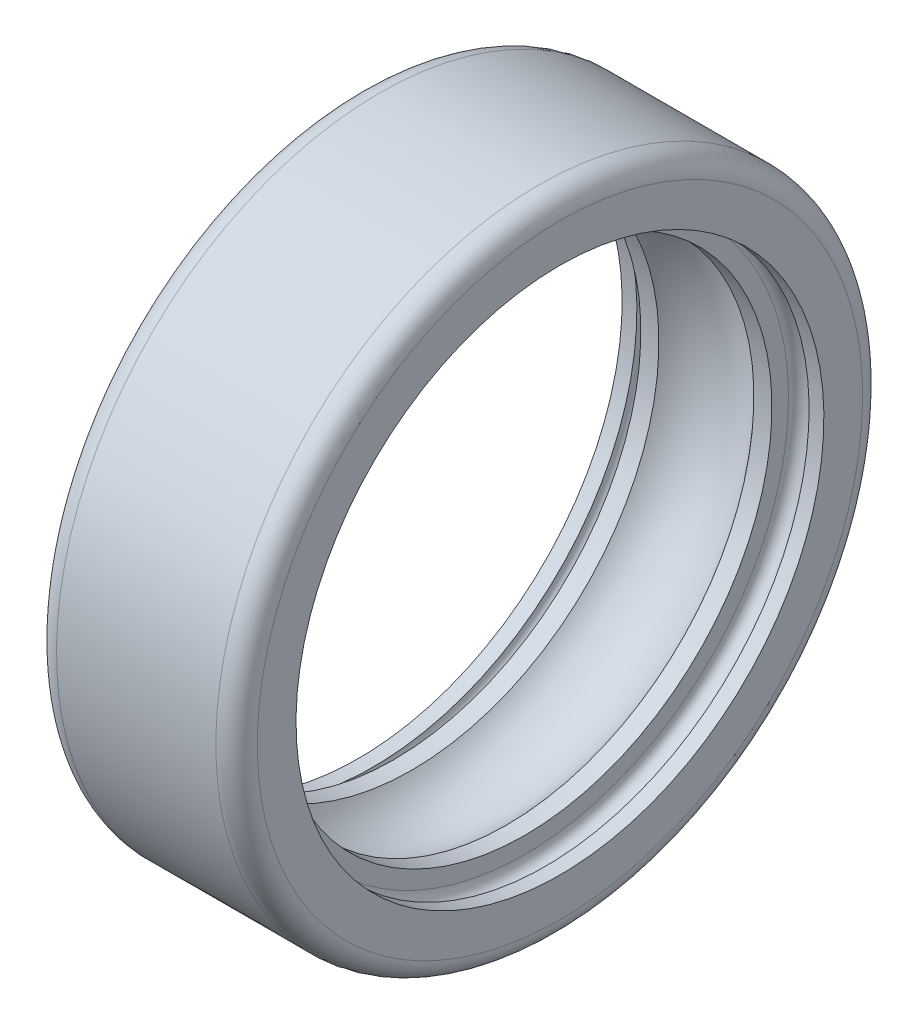
SolidWorks part; units mm, degrees
material "AISI 304"
ref_plane "Plano frontal" through (0, 0, 0) normal (0, 0, 1) x (1, 0, 0)
ref_plane "Plano superior" through (0, 0, 0) normal (0, 1, 0) x (1, 0, 0)
ref_plane "Plano direito" through (0, 0, 0) normal (1, 0, 0) x (0, 0, -1)
sketch "Esboço1" plane through (0, 0, 0) normal (0, 0, 1) x (1, 0, 0)
  line L0 (-22.7175, 2.9568) -> (-17.7175, 2.9568) construction
  line L2 (-1.9877, 2.5015) -> (1.957, 2.5015)
  line L3 (-2.4969, 3.0019) -> (-2.4969, 3.9651)
  line L4 (-1.9705, 8.0015) -> (1.9743, 8.0015)
  line L5 (2.5, 3.0019) -> (2.5, 3.9651)
  line L7 (-2.5, 6.5408) -> (-2.1334, 6.5408)
  line L8 (-1.6236, 6.5408) -> (-1.6236, 6.1298)
  line L9 (-1.6236, 6.1298) -> (-1.1769, 6.1298)
  line L10 (1.6236, 6.1298) -> (1.1769, 6.1298)
  line L11 (1.6236, 6.5408) -> (1.6236, 6.1298)
  line L12 (2.5, 6.5408) -> (2.1334, 6.5408)
  line L13 (-2.1884, 4.1901) -> (-2.1884, 6.0268)
  line L14 (-2.1184, 6.0968) -> (-1.7245, 6.0968)
  line L15 (-1.6545, 6.1668) -> (-1.6545, 6.4667)
  line L16 (-2.1145, 6.4667) -> (-2.1145, 6.3275)
  line L17 (-2.078, 6.2794) -> (-1.8845, 6.2794)
  line L18 (-1.8845, 6.2794) -> (-1.8845, 6.3794)
  line L19 (-1.8845, 6.3794) -> (-1.9445, 6.3794)
  line L20 (-2.0145, 6.4494) -> (-2.0145, 6.4667)
  line L21 (-1.7545, 6.4667) -> (-1.7545, 6.2668)
  line L22 (-1.8245, 6.1968) -> (-2.2192, 6.1968)
  line L23 (-2.1188, 4.1201) -> (-1.9112, 4.1201)
  line L24 (-1.9112, 4.1201) -> (-1.9112, 4.0201)
  line L25 (-1.9112, 4.0201) -> (-2.2184, 4.0201)
  line L26 (-2.2884, 4.0901) -> (-2.2884, 6.0268)
  line L27 (-2.2884, 6.0268) -> (-2.2884, 6.1371)
  line L28 (-2.5, 6.5408) -> (-2.5, 7.5)
  line L29 (2.5, 6.5408) -> (2.5, 7.5)
  line L30 (-2.4969, 3.9651) -> (-2.2384, 3.9651)
  line L31 (-2.2384, 3.9651) -> (-2.0732, 3.7803)
  line L32 (-2.0732, 3.7803) -> (-1.8146, 3.7803)
  line L33 (-1.8146, 3.7803) -> (-1.8146, 4.2124)
  line L34 (-1.8146, 4.2124) -> (-1.2851, 4.4263)
  line L35 (1.8146, 4.2124) -> (1.2851, 4.4263)
  line L36 (1.8146, 3.7803) -> (1.8146, 4.2124)
  line L37 (2.0732, 3.7803) -> (1.8146, 3.7803)
  line L38 (2.2384, 3.9651) -> (2.0732, 3.7803)
  line L39 (2.5, 3.9651) -> (2.2384, 3.9651)
  line L40 (0, 0.0015) -> (-3.7152, 0) construction
  line L41 (0, 0.0015) -> (0, 8) construction
  arc A0 (-2.1334, 6.5408) -> (-1.6236, 6.5408) centre (-1.8785, 6.5408) cw
  arc A1 (-1.2851, 4.4263) -> (1.2851, 4.4263) centre (0, 5.1999) ccw
  arc A2 (2.1334, 6.5408) -> (1.6236, 6.5408) centre (1.8785, 6.5408) ccw
  arc A3 (-2.1884, 6.0268) -> (-2.1184, 6.0968) centre (-2.1184, 6.0268) cw
  arc A4 (-1.6545, 6.4667) -> (-2.1145, 6.4667) centre (-1.8845, 6.4667) ccw
  arc A5 (-2.1145, 6.3275) -> (-2.078, 6.2794) centre (-2.0459, 6.3416) ccw
  arc A6 (-2.0145, 6.4667) -> (-1.7545, 6.4667) centre (-1.8845, 6.4667) cw
  arc A7 (-2.2192, 6.1968) -> (-2.2884, 6.1371) centre (-2.2192, 6.1268) ccw
  arc A8 (1.1769, 6.1298) -> (-1.1769, 6.1298) centre (0, 5.1999) ccw
  arc A9 (-1.9877, 2.5015) -> (-2.4969, 3.0019) centre (-1.9969, 3.0014) cw
  arc A10 (1.957, 2.5015) -> (2.5, 3.0019) centre (2, 2.9996) ccw
  arc A11 (1.9743, 8.0015) -> (2.5, 7.5) centre (2, 7.5021) cw
  arc A12 (-2.5, 7.5) -> (-1.9705, 8.0015) centre (-2, 7.5024) cw
  arc A13 (-2.1884, 4.1901) -> (-2.1188, 4.1201) centre (-2.1184, 4.1901) ccw
  arc A14 (-2.2184, 4.0201) -> (-2.2884, 4.0901) centre (-2.2184, 4.0901) cw
  arc A15 (-1.9445, 6.3794) -> (-2.0145, 6.4494) centre (-1.9445, 6.4494) cw
  arc A16 (-1.7545, 6.2668) -> (-1.8245, 6.1968) centre (-1.8245, 6.2668) cw
  arc A17 (-1.7245, 6.0968) -> (-1.6545, 6.1668) centre (-1.7245, 6.1668) ccw
  point P7 (0, 0)
  point P9 (0, 0)
  point P10 (0, 0)
  point P11 (0, 0)
  point P12 (0, 0)
  point P22 (0, 0)
  point P30 (-2.1145, 6.4667)
  point P52 (0, 0)
  point P53 (0, 0)
  point P58 (2.5, 2.75)
  point P61 (2.5, 7.75)
  point P64 (-2.5, 7.75)
  point P82 (2.3692, 3.9651)
  point P88 (0, 0)
  point P89 (0, 0)
  point P91 (0, 0)
  point P92 (0, 0)
  point P93 (0, 0)
  point P94 (0, 0)
  point P95 (0, 0)
  point P96 (0, 0)
  point P97 (0, 0)
  point P98 (0, 0)
  point P99 (0, 0)
  point P100 (0, 0)
  point P101 (2.22, 6.686)
  point P103 (-1.9445, 8)
  point P104 (-2.5, 7.5024)
  point P106 (-2.0648, 4.0201)
  point P107 (0, 0)
  point P112 (0, 0)
  point P113 (0, 0)
  point P114 (0, 0)
  point P115 (-2.2884, 6.0268)
  point P116 (-2.2884, 6.0268)
  point P117 (0, 0)
  point P118 (-2.2649, 6.1798)
  point P119 (-2.168, 4.1407)
  point P120 (-2.2884, 4.0901)
  point P121 (-2.2884, 4.0901)
  point P122 (-2.2884, 4.0901)
  point P123 (-2.2679, 4.0406)
  dimension "D4" = 4.0364
  dimension "D9" = 2.5
  dimension "D13" = 1.5
  dimension "D14" = 1.5
  dimension "D15" = 0.5701
  dimension "D16" = 0.4109
  dimension "D17" = 0.5295
  dimension "D21" = 0.2616
  dimension "D18" = 1.2058
  dimension "D35" = 7.0193
  dimension "D39" = 0.2085
  dimension "D40" = 0.3085
  dimension "D41" = 0.4439
  dimension "D42" = 0.3439
  dimension "D43" = 0.8455
  dimension "D6" = 0.3666
  dimension "D31" = 0.5
  dimension "D33" = 4.5
  dimension "D34" = 7.0228
  dimension "D51" = 0.07
  dimension "D52" = 0.07
  dimension "D63" = 0.07
  dimension "D64" = 0.07
  dimension "D72" = 0.3116
  dimension "D1" = 1.4607
  dimension "D2" = 2.5
  dimension "D3" = 8
  dimension "D5" = 5
  dimension "D7" = 1.8717
  dimension "D8" = 1.6236
  dimension "D10" = 1.6236
  dimension "D11" = 2.4969
  dimension "D12" = 2.5
  dimension "D19" = 1.2788
  dimension "D20" = 3.6292
  dimension "D22" = 0.1653
  dimension "D23" = 0.1653
  dimension "D24" = 0.2585
  dimension "D25" = 0.2584
  dimension "D26" = 0.4321
  dimension "D27" = 90
  dimension "D28" = 0.5
  dimension "D29" = 0.9632
  dimension "D30" = 3.9448
  dimension "D32" = 0.9592
  dimension "D36" = 1.5186
  dimension "D37" = 0.5857
  dimension "D38" = 1.6186
  dimension "D44" = 0.6155
  dimension "D45" = 0.23
  dimension "D46" = 0.1
  dimension "D47" = 0.1
  dimension "D48" = 0.1
  dimension "D49" = 0.2614
  dimension "D50" = 0.1935
  dimension "D53" = 0.2999
  dimension "D54" = 0.1999
  dimension "D55" = 0.1392
  dimension "D56" = 0.0173
  dimension "D57" = 0.6339
  dimension "D58" = 0.4173
  dimension "D59" = 0.0482
  dimension "D60" = 0.07
  dimension "D61" = 0.4999
  dimension "D62" = 0.06
  dimension "D65" = 0.3946
  dimension "D66" = 0.0692
  dimension "D67" = 0.1103
  dimension "D68" = 0.5139
  dimension "D69" = 0.3939
  dimension "D70" = 1.8368
  dimension "D71" = 0.2351
  dimension "D73" = 0.2076
  dimension "D74" = 0.07
  dimension "D75" = 0.1206
  dimension "D76" = 0.3567
revolve "Revolução1" add sketch "Esboço1" angle 360 about L40
